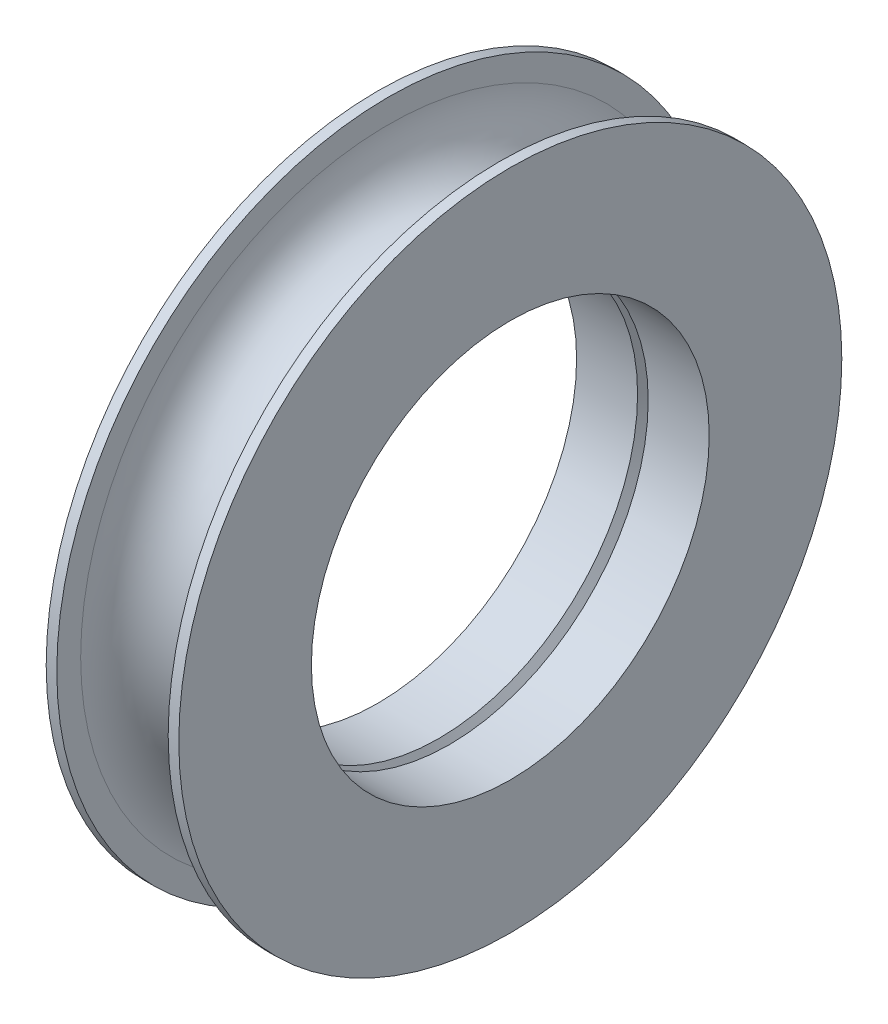
SolidWorks part; units mm, degrees
ref_plane "Front Plane" through (0, 0, 0) normal (0, 0, 1) x (1, 0, 0)
ref_plane "Top Plane" through (0, 0, 0) normal (0, 1, 0) x (1, 0, 0)
ref_plane "Right Plane" through (0, 0, 0) normal (1, 0, 0) x (0, 0, -1)
sketch "Sketch1" plane through (0, 0, 0) normal (0, 0, 1) x (1, 0, 0)
  line L0 (-2.5, 0) -> (2.5, 0) construction
  line L1 (-2.5, 7.5) -> (-0.2, 7.5)
  line L2 (2.5, 7.5) -> (2.5, 12.5)
  line L3 (2.5, 12.5) -> (2.1, 12.5)
  line L4 (-2.5, 7.5) -> (-2.5, 12.5)
  line L5 (-2.5, 12.5) -> (-2.1, 12.5)
  line L6 (-2.1, 11.6) -> (-2.1, 12.5)
  line L7 (2.1, 11.6) -> (2.1, 12.5)
  line L8 (0, 0) -> (0, 12.5) construction
  line L9 (-0.2, 7.5) -> (0, 7.8464)
  line L10 (0, 7.8464) -> (0.2, 7.5)
  line L11 (0.2, 7.5) -> (2.5, 7.5)
  line L12 (-2.5, 11.5) -> (2.5, 11.5) construction
  line L13 (-2.5, -11.5) -> (2.5, -11.5) construction
  arc A0 (-2.1, 11.6) -> (2.1, 11.6) centre (0, 11.6) ccw
  point P2 (0, 9.5)
  dimension "R" = 2.1
  dimension "P" = 15
  dimension "B" = 5
  dimension "D" = 25
  dimension "P.D." = 23
  dimension "D3" = 0.4
  dimension "D2" = 60
  dimension "D1." = 19
  dimension "D5" = 0.1
revolve "Revolve1" add sketch "Sketch1" angle 360 about L0
sketch "Sketch2" [suppressed] plane through (0, 0, 0) normal (0, 0, 1) x (1, 0, 0)
  line L0 (-2.5, 0) -> (2.5, 0) construction
  line L3 (-2.5, 12.5) -> (2.5, 12.5)
  line L4 (-2.5, 11.5) -> (2.5, 11.5) construction
  line L5 (-2.5, 12.5) -> (-2.5, 11.9)
  line L6 (-2.5, 7.5) -> (-2.5, 12.5) construction
  line L7 (2.5, 7.5) -> (2.5, 12.5) construction
  line L8 (-2.5, 11.9) -> (2.5, 11.9)
  line L9 (2.5, 12.5) -> (2.5, 11.9)
  line L10 (-2.5, 12.5) -> (-2.1, 12.5) construction
  dimension "MSM_6" = 0.4
  dimension "DC" = 23.8
revolve "Cut-Revolve1" [suppressed] cut sketch "Sketch2" angle 360 about L0
